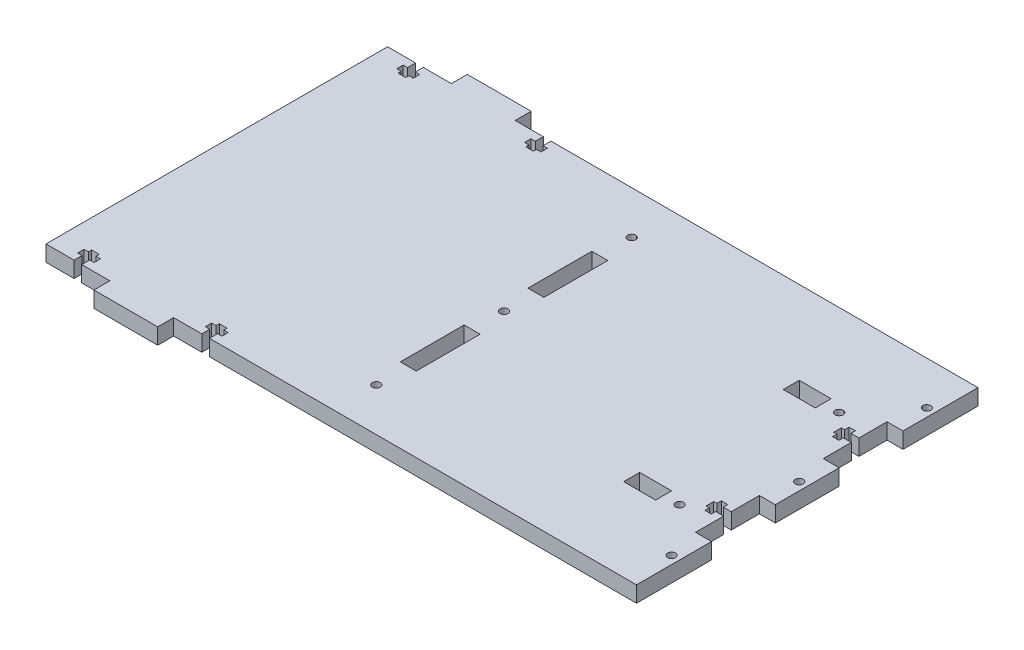
SolidWorks part; units mm, degrees
material "6061 Alloy"
ref_plane "Front Plane" through (0, 0, 0) normal (0, 0, 1) x (1, 0, 0)
ref_plane "Top Plane" through (0, 0, 0) normal (0, 1, 0) x (1, 0, 0)
ref_plane "Right Plane" through (0, 0, 0) normal (1, 0, 0) x (0, 0, -1)
sketch "Sketch1" plane through (0, 0, 0) normal (0, 1, 0) x (1, 0, 0)
  line L0 (-153.8491, 19.3709) -> (-153.8491, -116.5191)
  line L1 (-153.8491, -116.5191) -> (-142.673, -116.5191)
  line L2 (-139.6252, -116.5191) -> (-128.4491, -116.5191)
  line L3 (-103.0491, -116.5191) -> (-91.873, -116.5191)
  line L4 (-88.8252, -116.5191) -> (-77.6491, -116.5191)
  line L5 (-128.4491, -116.5191) -> (-128.4491, -122.8691)
  line L6 (-128.4491, -122.8691) -> (-103.0491, -122.8691)
  line L7 (-103.0491, -122.8691) -> (-103.0491, -116.5191)
  line L8 (-139.6252, -109.5341) -> (-139.6252, -110.8041)
  line L9 (-139.6252, -110.8041) -> (-137.8726, -110.8041)
  line L10 (-137.8726, -110.8041) -> (-137.8726, -113.3441)
  line L11 (-137.8726, -113.3441) -> (-139.6252, -113.3441)
  line L12 (-139.6252, -113.3441) -> (-139.6252, -116.5191)
  line L13 (-142.673, -109.5341) -> (-142.673, -110.8041)
  line L14 (-142.673, -110.8041) -> (-144.4256, -110.8041)
  line L15 (-144.4256, -110.8041) -> (-144.4256, -113.3441)
  line L16 (-144.4256, -113.3441) -> (-142.673, -113.3441)
  line L17 (-142.673, -113.3441) -> (-142.673, -116.5191)
  line L18 (-88.8252, -109.5341) -> (-88.8252, -110.8041)
  line L19 (-88.8252, -110.8041) -> (-87.0726, -110.8041)
  line L20 (-87.0726, -110.8041) -> (-87.0726, -113.3441)
  line L21 (-87.0726, -113.3441) -> (-88.8252, -113.3441)
  line L22 (-88.8252, -113.3441) -> (-88.8252, -116.5191)
  line L23 (-91.873, -109.5341) -> (-91.873, -110.8041)
  line L24 (-91.873, -110.8041) -> (-93.6256, -110.8041)
  line L25 (-93.6256, -110.8041) -> (-93.6256, -113.3441)
  line L26 (-93.6256, -113.3441) -> (-91.873, -113.3441)
  line L27 (-91.873, -113.3441) -> (-91.873, -116.5191)
  line L28 (-153.8491, 19.3709) -> (-142.673, 19.3709)
  line L29 (-139.6252, 19.3709) -> (-128.4491, 19.3709)
  line L30 (-103.0491, 19.3709) -> (-91.873, 19.3709)
  line L31 (-88.8252, 19.3709) -> (-77.6491, 19.3709)
  line L32 (-128.4491, 19.3709) -> (-128.4491, 25.7209)
  line L33 (-128.4491, 25.7209) -> (-103.0491, 25.7209)
  line L34 (-103.0491, 25.7209) -> (-103.0491, 19.3709)
  line L35 (-139.6252, 12.3859) -> (-139.6252, 13.6559)
  line L36 (-139.6252, 13.6559) -> (-137.8726, 13.6559)
  line L37 (-137.8726, 13.6559) -> (-137.8726, 16.1959)
  line L38 (-137.8726, 16.1959) -> (-139.6252, 16.1959)
  line L39 (-139.6252, 16.1959) -> (-139.6252, 19.3709)
  line L40 (-142.673, 12.3859) -> (-142.673, 13.6559)
  line L41 (-142.673, 13.6559) -> (-144.4256, 13.6559)
  line L42 (-144.4256, 13.6559) -> (-144.4256, 16.1959)
  line L43 (-144.4256, 16.1959) -> (-142.673, 16.1959)
  line L44 (-142.673, 16.1959) -> (-142.673, 19.3709)
  line L45 (-88.8252, 12.3859) -> (-88.8252, 13.6559)
  line L46 (-88.8252, 13.6559) -> (-87.0726, 13.6559)
  line L47 (-87.0726, 13.6559) -> (-87.0726, 16.1959)
  line L48 (-87.0726, 16.1959) -> (-88.8252, 16.1959)
  line L49 (-88.8252, 16.1959) -> (-88.8252, 19.3709)
  line L50 (-91.873, 12.3859) -> (-91.873, 13.6559)
  line L51 (-91.873, 13.6559) -> (-93.6256, 13.6559)
  line L52 (-93.6256, 13.6559) -> (-93.6256, 16.1959)
  line L53 (-93.6256, 16.1959) -> (-91.873, 16.1959)
  line L54 (-91.873, 16.1959) -> (-91.873, 19.3709)
  line L55 (-77.6491, 19.3709) -> (74.7509, 19.3709)
  line L56 (-77.6491, -116.5191) -> (74.7509, -116.5191)
  line L57 (-42.7241, -35.8741) -> (-36.3741, -35.8741)
  line L58 (-42.7241, -35.8741) -> (-42.7241, -10.4741)
  line L59 (-42.7241, -10.4741) -> (-36.3741, -10.4741)
  line L60 (-36.3741, -10.4741) -> (-36.3741, -35.8741)
  line L61 (-42.7241, -86.6741) -> (-36.3741, -86.6741)
  line L62 (-42.7241, -86.6741) -> (-42.7241, -61.2741)
  line L63 (-42.7241, -61.2741) -> (-36.3741, -61.2741)
  line L64 (-36.3741, -61.2741) -> (-36.3741, -86.6741)
  line L65 (74.7509, 19.3709) -> (81.1009, 19.3709)
  line L66 (74.7509, -116.5191) -> (81.1009, -116.5191)
  line L67 (74.7509, -35.8741) -> (81.1009, -35.8741)
  line L68 (74.7509, -35.8741) -> (74.7509, -24.6981)
  line L69 (74.7509, -21.6502) -> (74.7509, -10.4741)
  line L70 (74.7509, -10.4741) -> (81.1009, -10.4741)
  line L71 (74.7509, -86.6741) -> (81.1009, -86.6741)
  line L72 (74.7509, -86.6741) -> (74.7509, -75.4981)
  line L73 (74.7509, -72.4502) -> (74.7509, -61.2741)
  line L74 (74.7509, -61.2741) -> (81.1009, -61.2741)
  line L75 (81.1009, 19.3709) -> (81.1009, -10.4741)
  line L76 (81.1009, -35.8741) -> (81.1009, -61.2741)
  line L77 (81.1009, -86.6741) -> (81.1009, -116.5191)
  line L78 (67.7659, -24.6981) -> (69.0359, -24.6981)
  line L79 (69.0359, -24.6981) -> (69.0359, -26.4507)
  line L80 (69.0359, -26.4507) -> (71.5759, -26.4507)
  line L81 (71.5759, -26.4507) -> (71.5759, -24.6981)
  line L82 (71.5759, -24.6981) -> (74.7509, -24.6981)
  line L83 (67.7659, -21.6502) -> (69.0359, -21.6502)
  line L84 (69.0359, -21.6502) -> (69.0359, -19.8976)
  line L85 (69.0359, -19.8976) -> (71.5759, -19.8976)
  line L86 (71.5759, -19.8976) -> (71.5759, -21.6502)
  line L87 (71.5759, -21.6502) -> (74.7509, -21.6502)
  line L88 (67.7659, -75.4981) -> (69.0359, -75.4981)
  line L89 (69.0359, -75.4981) -> (69.0359, -77.2507)
  line L90 (69.0359, -77.2507) -> (71.5759, -77.2507)
  line L91 (71.5759, -77.2507) -> (71.5759, -75.4981)
  line L92 (71.5759, -75.4981) -> (74.7509, -75.4981)
  line L93 (67.7659, -72.4502) -> (69.0359, -72.4502)
  line L94 (69.0359, -72.4502) -> (69.0359, -70.6976)
  line L95 (69.0359, -70.6976) -> (71.5759, -70.6976)
  line L96 (71.5759, -70.6976) -> (71.5759, -72.4502)
  line L97 (71.5759, -72.4502) -> (74.7509, -72.4502)
  line L98 (-142.673, 12.3859) -> (-139.6252, 12.3859)
  line L99 (-91.873, 12.3859) -> (-88.8252, 12.3859)
  line L100 (-142.673, -109.5341) -> (-139.6252, -109.5341)
  line L101 (-91.873, -109.5341) -> (-88.8252, -109.5341)
  line L102 (67.7659, -21.6502) -> (67.7659, -24.6981)
  line L103 (67.7659, -72.4502) -> (67.7659, -75.4981)
  line L104 (49.3509, -77.1491) -> (43.0009, -77.1491)
  line L105 (43.0009, -77.1491) -> (43.0009, -83.4991)
  line L106 (43.0009, -83.4991) -> (55.7009, -83.4991)
  line L107 (55.7009, -83.4991) -> (55.7009, -77.1491)
  line L108 (55.7009, -77.1491) -> (49.3509, -77.1491)
  line L109 (49.3509, -19.9991) -> (43.0009, -19.9991)
  line L110 (43.0009, -19.9991) -> (43.0009, -13.6491)
  line L111 (43.0009, -13.6491) -> (55.7009, -13.6491)
  line L112 (55.7009, -13.6491) -> (55.7009, -19.9991)
  line L113 (55.7009, -19.9991) -> (49.3509, -19.9991)
  circle A0 centre (-39.5491, 2.2259) radius 1.5875
  circle A1 centre (-39.5491, -48.5741) radius 1.5875
  circle A2 centre (-39.5491, -99.3741) radius 1.5875
  circle A3 centre (77.9259, 2.2259) radius 1.5875
  circle A4 centre (77.9259, -48.5741) radius 1.5875
  circle A5 centre (77.9259, -99.3741) radius 1.5875
  circle A6 centre (62.0509, -80.3241) radius 1.5875
  circle A7 centre (62.0509, -16.8241) radius 1.5875
extrude "Boss-Extrude1" add sketch "Sketch1" along normal blind 6.35
